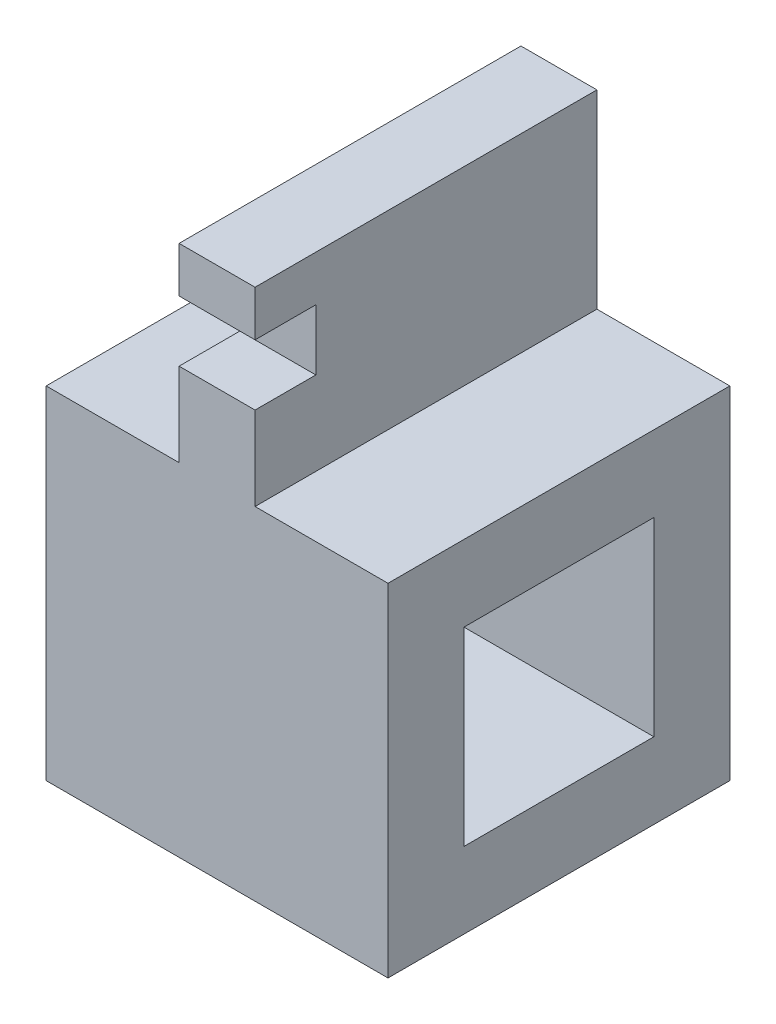
SolidWorks part; units mm, degrees
ref_plane "Front Plane" through (0, 0, 0) normal (0, 0, 1) x (1, 0, 0)
ref_plane "Top Plane" through (0, 0, 0) normal (0, 1, 0) x (1, 0, 0)
ref_plane "Right Plane" through (0, 0, 0) normal (1, 0, 0) x (0, 0, -1)
sketch "Sketch1" plane through (0, 0, 0) normal (1, 0, 0) x (0, 0, -1)
  line L1 (4.5, -4.5) -> (-4.5, -4.5)
  line L2 (4.5, -4.5) -> (4.5, 4.5)
  line L3 (4.5, 4.5) -> (-4.5, 4.5)
  line L4 (-4.5, -4.5) -> (-4.5, 4.5)
  line L5 (0, 4.5) -> (0, -4.5) construction
  line L6 (4.5, 0) -> (-4.5, 0) construction
  line L7 (2.5, -2.5) -> (-2.5, -2.5)
  line L8 (2.5, -2.5) -> (2.5, 2.5)
  line L9 (2.5, 2.5) -> (-2.5, 2.5)
  line L10 (-2.5, -2.5) -> (-2.5, 2.5)
  line L11 (0, 2.5) -> (0, -2.5) construction
  line L12 (2.5, 0) -> (-2.5, 0) construction
  point P0 (0, 0)
  point P4 (0, 0)
  dimension "D1" = 9
  dimension "D2" = 9
  dimension "D3" = 5
  dimension "D4" = 5
extrude "Boss-Extrude1" add sketch "Sketch1" along normal blind 9
sketch "Sketch2" plane through (0, 4.5, 0) normal (0, 1, 0) x (1, 0, 0)
  line L1 (5.5, -4.5) -> (3.5, -4.5)
  line L3 (9, -1) -> (9, 1)
  line L4 (0, 4.5) -> (0, -4.5)
  line L5 (0, -4.5) -> (9, -4.5)
  line L6 (9, -4.5) -> (9, 4.5)
  line L7 (9, 4.5) -> (0, 4.5)
  line L8 (0, 4.5) -> (0, -4.5)
  line L9 (0, -4.5) -> (9, -4.5)
  line L10 (9, -4.5) -> (9, 4.5)
  line L11 (9, 4.5) -> (0, 4.5)
  line L13 (0, -1) -> (0, 1)
  line L14 (4.5, 1) -> (4.5, -1) construction
  line L15 (5.5, -4.5) -> (5.5, 4.5)
  line L16 (5.5, 4.5) -> (3.5, 4.5)
  line L17 (3.5, -4.5) -> (3.5, 4.5)
  line L18 (4.5, 4.5) -> (4.5, -4.5) construction
  line L19 (5.5, 0) -> (3.5, 0) construction
  point P2 (4.5, 0)
  point P6 (4.5, 0)
  line M8 (0, -4.5) -> (9, -4.5)
  dimension "D2" = 2
  dimension "D3" = 4.5
  dimension "D1" = 0
extrude "Boss-Extrude2" add sketch "Sketch2" along normal blind 5 contours L17 L15 L11 M8
sketch "Sketch4" plane through (3.5, 0, 0) normal (-1, 0, 0) x (0, 0, 1)
  line L0 (-4.5, 7.5) -> (4.5, 7.5) construction
  line L2 (2.9, 6.7) -> (4.5, 6.7)
  line L3 (2.9, 6.7) -> (2.9, 8.3)
  line L4 (-4.5, 4.5) -> (4.5, 4.5)
  line L5 (4.5, 4.5) -> (4.5, 9.5)
  line L6 (4.5, 9.5) -> (-4.5, 9.5)
  line L7 (-4.5, 9.5) -> (-4.5, 4.5)
  line L8 (-4.5, 4.5) -> (4.5, 4.5)
  line L9 (4.5, 4.5) -> (4.5, 9.5)
  line L10 (4.5, 9.5) -> (-4.5, 9.5)
  line L11 (-4.5, 9.5) -> (-4.5, 4.5)
  line L12 (2.9, 8.3) -> (4.5, 8.3)
  line L13 (4.5, 6.7) -> (4.5, 8.3)
  line L14 (3.7, 8.3) -> (3.7, 6.7) construction
  line L15 (2.9, 7.5) -> (4.5, 7.5) construction
  point P6 (3.7, 7.5)
  line M9 (4.5, 4.5) -> (4.5, 9.5)
  dimension "D2" = 1.6
  dimension "D3" = 1.6
  dimension "D4" = 1.2
  dimension "D1" = 0
extrude "Cut-Extrude2" cut sketch "Sketch4" against normal blind 5 contours L12 L3 L2 M9
